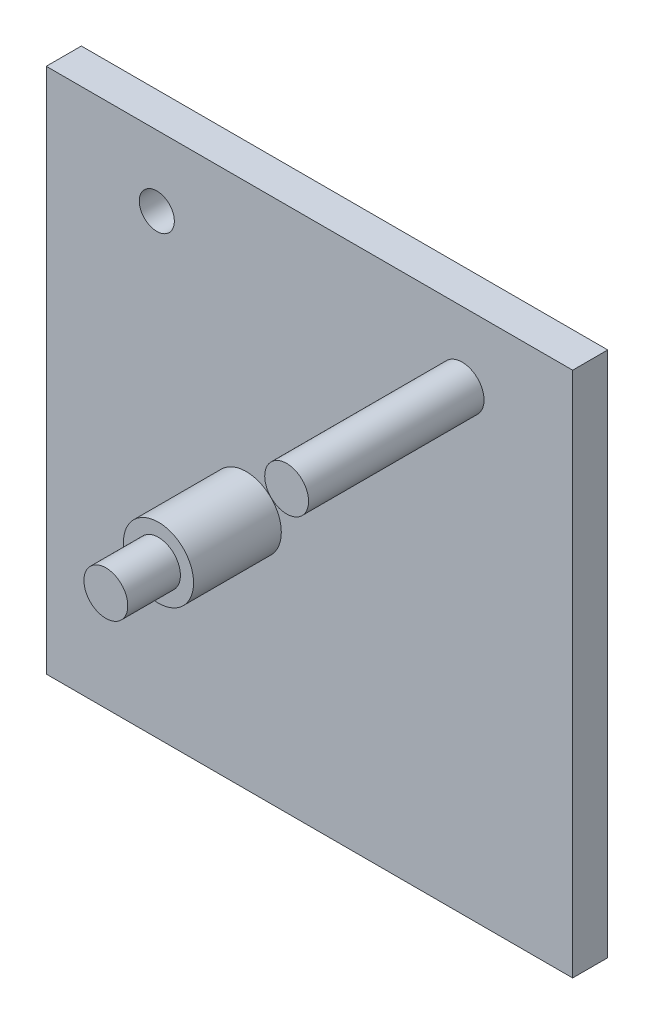
SolidWorks part; units mm, degrees
ref_plane "Front Plane" through (0, 0, 0) normal (0, 0, 1) x (1, 0, 0)
ref_plane "Top Plane" through (0, 0, 0) normal (0, 1, 0) x (1, 0, 0)
ref_plane "Right Plane" through (0, 0, 0) normal (1, 0, 0) x (0, 0, -1)
sketch "Sketch1" plane through (0, 0, 0) normal (0, 0, 1) x (1, 0, 0)
  line L0 (-38.1, 24.5752) -> (-38.1, -13.5248)
  line L3 (0, 24.5752) -> (-38.1, 24.5752)
  line L6 (-38.1, -13.5248) -> (0, -13.5248)
  line L7 (0, -13.5248) -> (0, 24.5752)
  point P0 (-19.05, 24.5752)
  dimension "D1" = 38.1
  dimension "D2" = 38.1
  dimension "D3" = 90
extrude "Boss-Extrude1" add sketch "Sketch1" along normal blind 2.54 contours L3 L0 L6 L7
sketch "Sketch2" plane through (0, 0, 2.54) normal (0, 0, 1) x (1, 0, 0)
  line L0 (0, -13.5248) -> (0, 24.5752) construction
  line L1 (0, 24.5752) -> (-38.1, 24.5752) construction
  line L2 (0, 19.4952) -> (-38.1, 19.4952) construction
  line L3 (-8.001, 19.4952) -> (-30.099, 19.4952) construction
  line L7 (-38.1, 24.5752) -> (-38.1, -13.5248) construction
  line L8 (-8.001, 19.4952) -> (-23.6266, 3.8695) construction
  circle A1 centre (-8.001, 19.4952) radius 1.5875
  circle A2 centre (-23.6266, 3.8695) radius 1.5875
  circle A3 centre (-30.099, 19.4952) radius 1.27
  point P1 (0, 0)
  point P4 (-19.05, 19.4952)
  point P5 (-19.05, 19.4952)
  point P8 (-19.05, 24.5752)
  point P12 (0, 0)
  point P14 (-19.05, 19.4952)
  dimension "D1" = 3.175
  dimension "D2" = 2.54
  dimension "D3" = 5.08
  dimension "D4" = 45
  dimension "D6" = 3.175
  dimension "D5" = 22.098
  dimension "D7" = 22.098
extrude "Boss-Extrude2" add sketch "Sketch2" along normal blind 12.7
sketch "Sketch5" plane through (0, 0, 15.24) normal (0, 0, 1) x (1, 0, 0)
  circle A0 centre (-30.099, 19.4952) radius 1.27
  dimension "D1" = 2.54
extrude "Cut-Extrude1" cut sketch "Sketch5" against normal through all
sketch "Sketch6" plane through (0, 0, 2.54) normal (0, 0, 1) x (1, 0, 0)
  circle A0 centre (-23.6266, 3.8695) radius 2.54
  dimension "D1" = 5.08
extrude "Boss-Extrude3" add sketch "Sketch6" along normal blind 6.35
sketch "Sketch7" plane through (0, 0, 15.24) normal (0, 0, 1) x (1, 0, 0)
  circle A1 centre (-23.6266, 3.8695) radius 1.5875
  dimension "D1" = 3.175
extrude "Cut-Extrude2" cut sketch "Sketch7" against normal blind 2.54
